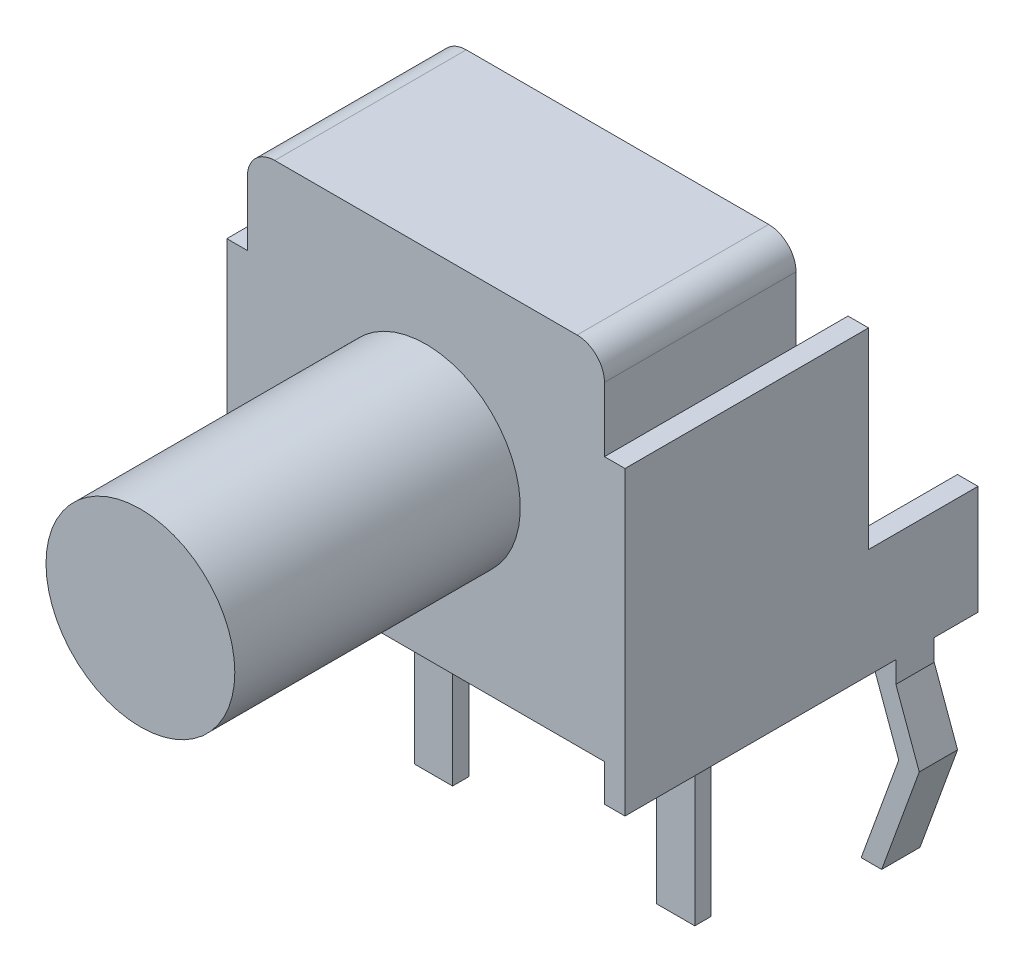
SolidWorks part; units mm, degrees
ref_plane "front" through (0, 0, 0) normal (0, 0, 1) x (1, 0, 0)
ref_plane "top" through (0, 0, 0) normal (0, 1, 0) x (1, 0, 0)
ref_plane "right" through (0, 0, 0) normal (1, 0, 0) x (0, 0, -1)
sketch "Sketch2" plane through (0, 0, 0) normal (1, 0, 0) x (0, 0, -1)
  line L0 (0, 0) -> (5.0292, 0)
  line L1 (5.0292, 0) -> (5.0292, -3.5052)
  line L2 (5.0292, -3.5052) -> (5.7404, -3.5052)
  line L3 (5.7404, -3.5052) -> (5.7404, 0)
  line L4 (5.7404, 0) -> (6.5532, 0)
  line L5 (6.5532, 0) -> (6.5532, 2.025)
  line L6 (6.5532, 2.025) -> (4.5212, 2.025)
  line L7 (4.5212, 2.025) -> (4.5212, 5.588)
  line L8 (4.5212, 5.588) -> (3.556, 5.588)
  line L9 (3.556, 5.588) -> (3.556, 7.62)
  line L10 (3.556, 7.62) -> (0, 7.62)
  line L11 (0, 7.62) -> (0, 0)
  dimension "D1" = 0.7112
  dimension "D2" = 3.5052
  dimension "D3" = 5.0292
  dimension "D4" = 6.5532
  dimension "D5" = 3.556
  dimension "D6" = 2.032
  dimension "D7" = 7.62
  dimension "D8" = 5.588
extrude "Extrude2" add sketch "Sketch2" along normal mid plane 12.7
sketch "Sketch3" plane through (0, 0, 0) normal (0, 0, 1) x (1, 0, 0)
  line L0 (-3.3147, 0.6858) -> (3.3147, 0.6858)
  line L1 (3.3147, 0.6858) -> (3.3147, -0.397)
  line L2 (3.3147, -0.397) -> (3.7483, -1.5884)
  line L3 (3.7483, -1.5884) -> (2.9783, -3.7041)
  line L4 (2.9783, -3.7041) -> (3.3147, -3.8265)
  line L5 (3.3147, -3.8265) -> (4.1293, -1.5884)
  line L6 (4.1293, -1.5884) -> (3.6957, -0.397)
  line L7 (3.6957, -0.397) -> (3.6957, 5.588)
  line L8 (3.6957, 5.588) -> (3.3147, 5.588)
  line L9 (3.3147, 5.588) -> (3.3147, 6.7818)
  line L10 (2.8067, 7.2898) -> (-2.8067, 7.2898)
  line L11 (0, -4.5777) -> (0, -7.1976) construction
  line L12 (-3.3147, 5.588) -> (-3.3147, 6.7818)
  line L13 (-3.6957, 5.588) -> (-3.3147, 5.588)
  line L14 (-3.6957, -0.397) -> (-3.6957, 5.588)
  line L15 (-4.1293, -1.5884) -> (-3.6957, -0.397)
  line L16 (-3.3147, -3.8265) -> (-4.1293, -1.5884)
  line L17 (-2.9783, -3.7041) -> (-3.3147, -3.8265)
  line L18 (-3.7483, -1.5884) -> (-2.9783, -3.7041)
  line L19 (-3.3147, -0.397) -> (-3.7483, -1.5884)
  line L20 (-3.3147, 0.6858) -> (-3.3147, -0.397)
  arc A0 (3.3147, 6.7818) -> (2.8067, 7.2898) centre (2.8067, 6.7818) ccw
  arc A1 (-3.3147, 6.7818) -> (-2.8067, 7.2898) centre (-2.8067, 6.7818) cw
  circle A2 centre (0, 3.9878) radius 3.302 construction
  dimension "D4" = 0.508
  dimension "D6" = 6.604
  dimension "D1" = 0.381
  dimension "D2" = 20
  dimension "D3" = 40
  dimension "D5" = 7.3914
  dimension "D7" = 3.9878
extrude "Cut-Extrude1" cut sketch "Sketch3" against normal mid plane 15.24 flip side to cut
sketch "Sketch4" plane through (0, 0, 0) normal (0, 1, 0) x (1, 0, 0)
  line L0 (3.3147, 6.5532) -> (3.3147, 0) construction
  line L1 (-3.3147, 9.5151) -> (3.3147, 9.5151)
  line L2 (-3.3147, 9.5151) -> (-3.3147, 3.556)
  line L3 (-3.3147, 3.556) -> (3.3147, 3.556)
  line L4 (3.3147, 9.5151) -> (3.3147, 3.556)
  line L5 (-3.3147, 6.5532) -> (-3.3147, 0) construction
  line L7 (2.8067, 3.556) -> (-2.8067, 3.556) construction
extrude "Cut-Extrude2" cut sketch "Sketch4" along normal blind 12.7
sketch "Sketch5" plane through (0, 0, 0) normal (0, 1, 0) x (1, 0, 0)
  line L0 (0, -0.7203) -> (0, -3.0511) construction
  line L1 (1.8923, 2.3876) -> (2.6035, 2.3876)
  line L2 (1.8923, 2.3876) -> (1.8923, 2.6924)
  line L3 (1.8923, 2.6924) -> (2.6035, 2.6924)
  line L4 (2.6035, 2.3876) -> (2.6035, 2.6924)
  line L5 (-2.6035, 2.3876) -> (-2.6035, 2.6924)
  line L6 (-1.8923, 2.6924) -> (-2.6035, 2.6924)
  line L7 (-1.8923, 2.3876) -> (-1.8923, 2.6924)
  line L8 (-1.8923, 2.3876) -> (-2.6035, 2.3876)
  point P4 (2.2479, 2.6924)
  point P5 (2.6035, 2.54)
  point P8 (-2.6035, 2.54)
  point P10 (-2.2479, 2.6924)
  dimension "D1" = 0.7112
  dimension "D2" = 0.3048
  dimension "D3" = 2.54
  dimension "D4" = 4.4958
extrude "Extrude3" add sketch "Sketch5" along normal blind 2.54 and the other way blind 3.5052
sketch "Sketch6" plane through (0, 0, 0) normal (0, 0, 1) x (1, 0, 0)
  circle A0 centre (0, 3.9878) radius 1.7526
  dimension "D1" = 3.5052
  dimension "D2" = 3.9878
extrude "Extrude4" add sketch "Sketch6" along normal blind 5.3
